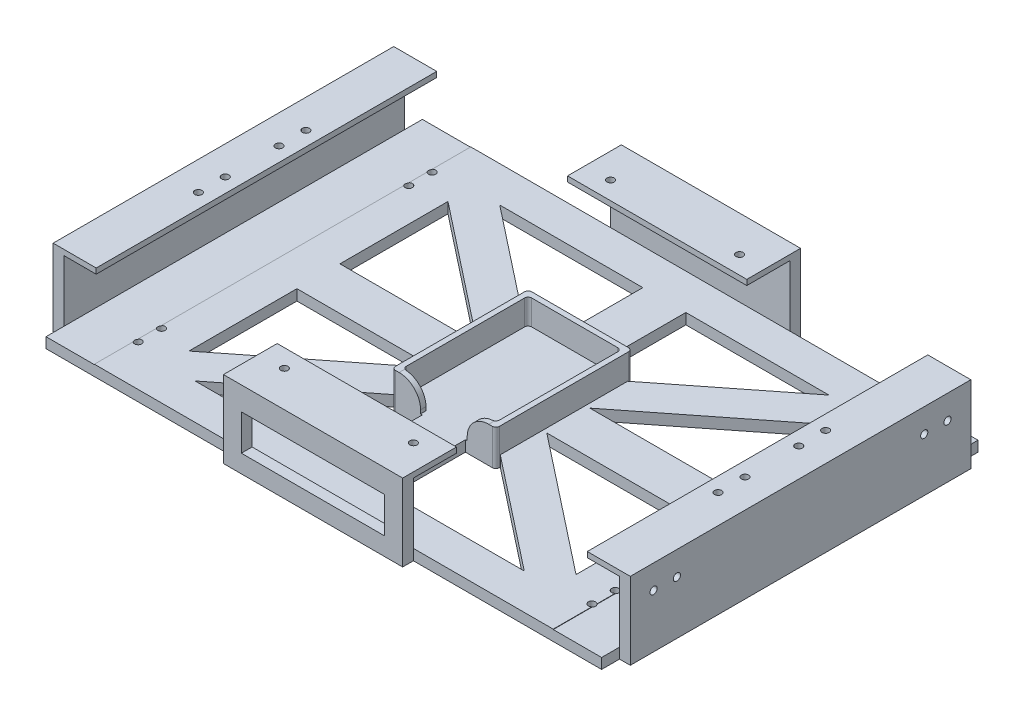
SolidWorks part; units mm, degrees
ref_plane "Front Plane" through (0, 0, 0) normal (0, 0, 1) x (1, 0, 0)
ref_plane "Top Plane" through (0, 0, 0) normal (0, 1, 0) x (1, 0, 0)
ref_plane "Right Plane" through (0, 0, 0) normal (1, 0, 0) x (0, 0, -1)
sketch "Sketch1" plane through (0, 0, 0) normal (0, 1, 0) x (1, 0, 0)
  line L1 (-77.5, -52.5) -> (77.5, -52.5)
  line L2 (-77.5, -52.5) -> (-77.5, 52.5)
  line L3 (-77.5, 52.5) -> (77.5, 52.5)
  line L4 (77.5, -52.5) -> (77.5, 52.5)
  line L5 (-77.5, -52.5) -> (77.5, 52.5) construction
  line L6 (-77.5, 52.5) -> (77.5, -52.5) construction
  line L7 (-77.5, -52.5) -> (-64, -52.5)
  line L8 (-77.5, -52.5) -> (-77.5, 52.5)
  line L9 (-77.5, 52.5) -> (-64, 52.5)
  line L10 (-64, -52.5) -> (-64, 52.5)
  line L11 (77.5, -52.5) -> (64, -52.5)
  line L12 (77.5, -52.5) -> (77.5, 52.5)
  line L13 (77.5, 52.5) -> (64, 52.5)
  line L14 (64, -52.5) -> (64, 52.5)
  point P0 (0, 0)
  dimension "D1" = 155
  dimension "D2" = 105
  dimension "D3" = 13.5
  dimension "D4" = 13.5
extrude "Boss-Extrude1" add sketch "Sketch1" along normal blind 3 contours L1 L14 L3 L10
sketch "Sketch2" plane through (0, 0, 0) normal (0, 1, 0) x (1, 0, 0)
  line L0 (-64, 52.5) -> (64, 52.5) construction
  line L1 (-64, 52.5) -> (-77.5, 52.5)
  line L2 (-64, 52.5) -> (-64, -52.5)
  line L3 (-64, -52.5) -> (-77.5, -52.5)
  line L4 (-77.5, 52.5) -> (-77.5, -52.5)
  line L5 (64, -52.5) -> (77.5, -52.5)
  line L6 (64, -52.5) -> (64, 52.5)
  line L7 (64, 52.5) -> (77.5, 52.5)
  line L8 (77.5, -52.5) -> (77.5, 52.5)
  dimension "D1" = 105
  dimension "D2" = 105
  dimension "D3" = 13.5
  dimension "D4" = 13.5
extrude "Boss-Extrude2" add sketch "Sketch2" along normal blind 2.9
sketch "Sketch3" plane through (0, 0, 0) normal (0, 1, 0) x (1, 0, 0)
  line L0 (-77.5, 52.5) -> (-77.5, -52.5) construction
  line L1 (-77.5, 47.5) -> (-80.5, 47.5)
  line L2 (-77.5, 47.5) -> (-77.5, -47.5)
  line L3 (-77.5, -47.5) -> (-80.5, -47.5)
  line L4 (-80.5, 47.5) -> (-80.5, -47.5)
  line L5 (77.5, -52.5) -> (77.5, 52.5) construction
  line L6 (77.5, -47.5) -> (80.5, -47.5)
  line L7 (77.5, -47.5) -> (77.5, 47.5)
  line L8 (77.5, 47.5) -> (80.5, 47.5)
  line L9 (80.5, -47.5) -> (80.5, 47.5)
  line L10 (-77.5, -52.5) -> (-64, -52.5) construction
  dimension "D1" = 95
  dimension "D2" = 5
  dimension "D3" = 0
  dimension "D4" = 0
  dimension "D5" = 3
  dimension "D6" = 3
sketch "Sketch4" plane through (0, 0, 0) normal (0, 1, 0) x (1, 0, 0)
  line L0 (-64, -52.5) -> (64, -52.5) construction
  line L1 (-25, -52.5) -> (25, -52.5)
  line L2 (0, -52.5) -> (0, -55.5)
  line L3 (-25, -55.5) -> (25, -55.5)
  line L4 (25, -52.5) -> (25, -55.5)
  line L5 (0, 0) -> (0, -14.14) construction
  line L6 (0, -14.14) -> (0, 0) construction
  line L7 (0, 0) -> (18.2172, 0) construction
  line L8 (-25, -52.5) -> (-25, -55.5)
  line L9 (-25, 52.5) -> (-25, 55.5)
  line L10 (-25, 52.5) -> (25, 52.5)
  line L11 (25, 52.5) -> (25, 55.5)
  line L12 (-25, 55.5) -> (25, 55.5)
  dimension "D1" = 25
  dimension "D2" = 3
sketch "Sketch5" plane through (0, 3, 0) normal (0, 1, 0) x (1, 0, 0)
  line L0 (-6.5, -17.5) -> (-6.5, -19)
  line L1 (-13, -17.5) -> (13, -17.5)
  line L2 (-13, -17.5) -> (-13, 17.5)
  line L3 (-13, 17.5) -> (13, 17.5)
  line L4 (13, -17.5) -> (13, 17.5)
  line L5 (-13, -17.5) -> (13, 17.5) construction
  line L6 (-13, 17.5) -> (13, -17.5) construction
  line L7 (-14.5, -19) -> (14.5, -19)
  line L8 (-14.5, -19) -> (-14.5, 19)
  line L9 (-14.5, 19) -> (14.5, 19)
  line L10 (14.5, -19) -> (14.5, 19)
  line L11 (-14.5, -19) -> (14.5, 19) construction
  line L12 (-14.5, 19) -> (14.5, -19) construction
  line L13 (6.5, -17.5) -> (6.5, -19)
  line L14 (0, 0) -> (0, -10.4966)
  point P0 (0, 0)
  point P6 (0, 0)
  dimension "D1" = 26
  dimension "D2" = 35
  dimension "D3" = 1.5
  dimension "D4" = 1.5
  dimension "D5" = 8
extrude "Boss-Extrude9" add sketch "Sketch5" along normal blind 7 contours L1 L13 L7 L10 L9 L8 L0 L2 L3 L4
fillet "Fillet1" radius 6 2 edges at (-6.5, 10, 18.25) (6.5, 10, 18.25)
fillet "Fillet2" radius 1 8 edges at (-13, 6.5, 17.5) (13, 6.5, 17.5) (-13, 6.5, -17.5) (14.5, 6.5, -19) (14.5, 6.5, 19) (13, 6.5, -17.5) (-14.5, 6.5, -19) (-14.5, 6.5, 19)
sketch "Sketch10" plane through (0, 3, 0) normal (0, 1, 0) x (1, 0, 0)
  line L0 (-64, -52.5) -> (-64, 52.5) construction
  line L1 (-54, -42.5) -> (54, -42.5)
  line L2 (-54, -42.5) -> (-54, 42.5)
  line L3 (-54, 42.5) -> (54, 42.5)
  line L4 (54, -42.5) -> (54, 42.5)
  line L5 (-54, -42.5) -> (54, 42.5) construction
  line L6 (-54, 42.5) -> (54, -42.5) construction
  line L7 (-64, 52.5) -> (64, 52.5) construction
  line L8 (-54, 36.1372) -> (45.9155, -42.5)
  line L9 (-45.9155, -42.5) -> (54, 36.1372)
  line L10 (-54, -36.1372) -> (45.9155, 42.5)
  line L11 (-45.9155, 42.5) -> (54, -36.1372)
  line L12 (-6.5, -19) -> (6.5, -19)
  line L13 (-54, -6) -> (54, -6)
  line L14 (-54, -6) -> (-54, 6)
  line L15 (-54, 6) -> (54, 6)
  line L16 (54, -6) -> (54, 6)
  line L17 (-54, -6) -> (54, 6) construction
  line L18 (-54, 6) -> (54, -6) construction
  line L19 (-6, 42.5) -> (6, 42.5)
  line L20 (-6, 42.5) -> (-6, -42.5)
  line L21 (-6, -42.5) -> (6, -42.5)
  line L22 (6, 42.5) -> (6, -42.5)
  line L23 (-6, 42.5) -> (6, -42.5) construction
  line L24 (-6, -42.5) -> (6, 42.5) construction
  point P0 (0, 0)
  point P18 (0, 0)
  point P23 (0, 0)
  line M19 (-6.5, -19) -> (-13.5, -19)
  arc M20 (-13.5, -19) -> (-14.5, -18) centre (-13.5, -18) cw
  line M21 (-14.5, -18) -> (-14.5, 18)
  arc M22 (-14.5, 18) -> (-13.5, 19) centre (-13.5, 18) cw
  line M23 (-13.5, 19) -> (13.5, 19)
  arc M24 (13.5, 19) -> (14.5, 18) centre (13.5, 18) cw
  line M25 (14.5, 18) -> (14.5, -18)
  arc M26 (14.5, -18) -> (13.5, -19) centre (13.5, -18) cw
  line M27 (13.5, -19) -> (6.5, -19)
  dimension "D1" = 10
  dimension "D2" = 10
  dimension "D3" = 5
  dimension "D4" = 5
  dimension "D5" = 10
  dimension "D6" = 10
  dimension "D7" = 12
  dimension "D8" = 12
extrude "Cut-Extrude1" cut sketch "Sketch10" against normal blind 7 contours L2 L15 L8 | L20 L3 L11 M21 M22 M23 | L3 L22 L10 M23 M24 M25 | L9 L15 L4 | L13 L11 L4 | L12 L22 L1 L8 M25 M26 M27 | L20 L12 L9 L1 M19 M20 M21 | L13 L2 L10
extrude "Boss-Extrude10" add sketch "Sketch3" along normal blind 20
sketch "Sketch11" plane through (0, 3, 0) normal (0, 1, 0) x (1, 0, 0)
  line L0 (-64, -52.5) -> (-64, -42.5)
  line L1 (-64, -52.5) -> (-64, 52.5) construction
  line L2 (-64, -42.5) -> (-63.3, -42.5)
  line L3 (-63.3, -39.5) -> (-63.3, -36)
  line L4 (-63.3, -33) -> (-64, -33)
  line L5 (0, 0) -> (29.0728, 0) construction
  line L6 (29.0728, 0) -> (0, 0) construction
  line L7 (0, 0) -> (0, 24.7559) construction
  line L8 (-63.3, 33) -> (-64, 33)
  line L9 (-63.3, 39.5) -> (-63.3, 36)
  line L10 (-64, 42.5) -> (-63.3, 42.5)
  line L11 (64, 42.5) -> (63.3, 42.5)
  line L12 (63.3, 39.5) -> (63.3, 36)
  line L13 (63.3, 33) -> (64, 33)
  line L14 (63.3, -33) -> (64, -33)
  line L15 (63.3, -39.5) -> (63.3, -36)
  line L16 (64, -42.5) -> (63.3, -42.5)
  arc A0 (-63.3, -42.5) -> (-63.3, -39.5) centre (-63.3, -41) ccw
  circle A1 centre (-63.3, -41) radius 1
  arc A2 (-63.3, -36) -> (-63.3, -33) centre (-63.3, -34.5) ccw
  circle A3 centre (-63.3, -34.5) radius 1
  circle A4 centre (-63.3, 34.5) radius 1
  arc A5 (-63.3, 36) -> (-63.3, 33) centre (-63.3, 34.5) cw
  circle A6 centre (-63.3, 41) radius 1
  arc A7 (-63.3, 42.5) -> (-63.3, 39.5) centre (-63.3, 41) cw
  arc A8 (63.3, 42.5) -> (63.3, 39.5) centre (63.3, 41) ccw
  circle A9 centre (63.3, 41) radius 1
  arc A10 (63.3, 36) -> (63.3, 33) centre (63.3, 34.5) ccw
  circle A11 centre (63.3, 34.5) radius 1
  circle A12 centre (63.3, -34.5) radius 1
  arc A13 (63.3, -36) -> (63.3, -33) centre (63.3, -34.5) cw
  circle A14 centre (63.3, -41) radius 1
  arc A15 (63.3, -42.5) -> (63.3, -39.5) centre (63.3, -41) cw
  dimension "D3" = 1.5
  dimension "D4" = 2
  dimension "D6" = 1.5
  dimension "D7" = 2
  dimension "D1" = 10
  dimension "D2" = 0.7
  dimension "D5" = 3.5
  dimension "D8" = 6.5
extrude "Cut-Extrude2" cut sketch "Sketch11" against normal blind 20 contours A1 | A3 | A6 | A4 | A9 | A11 | A14 | A12
sketch "Sketch13" plane through (-77.5, 0, 0) normal (1, 0, 0) x (0, 0, -1)
  line L0 (-42.5, 14.8425) -> (-39.5, 14.8425)
  line L1 (-52.5, 2.9) -> (-42.5, 2.9)
  line L2 (-42.5, 2.6425) -> (-42.5, 14.8425)
  line L4 (-39.5, 14.8425) -> (-36, 14.8425)
  arc A0 (-42.5, 14.8425) -> (-39.5, 14.8425) centre (-41, 14.8425) cw
  circle A1 centre (-41, 14.8425) radius 1
  arc A2 (-36, 14.8425) -> (-33, 14.8425) centre (-34.5, 14.8425) cw
  circle A3 centre (-34.5, 14.8425) radius 1
  dimension "D3" = 1.5
  dimension "D4" = 2
  dimension "D6" = 1.5
  dimension "D7" = 2
  dimension "D1" = 10
  dimension "D2" = 12.2
  dimension "D5" = 3.5
extrude "Cut-Extrude3" cut sketch "Sketch13" against normal blind 20 contours A1 | A3
mirror "Mirror1" about plane through (0, 0, 0) normal (0, 0, 1) of "Cut-Extrude3" second plane through (0, 0, 0) second plane normal (1, 0, 0)
extrude "Boss-Extrude11" add sketch "Sketch4" along normal blind 20 contours L12 L9 L10 L11 | L1 L8 L3 L2 | L4 L1 L2 L3
sketch "Sketch14" plane through (0, 0, 55.5) normal (0, 0, 1) x (1, 0, 0)
  line L0 (0, 0) -> (0, 20) construction
  line L1 (-25, 20) -> (25, 20) construction
  line L3 (25, 20) -> (25, 0) construction
  line L4 (25, 10) -> (-25, 10) construction
  line L5 (-25, 20) -> (-25, 0) construction
  line L6 (-20, 5) -> (20, 5)
  line L7 (-20, 5) -> (-20, 15)
  line L8 (-20, 15) -> (20, 15)
  line L9 (20, 5) -> (20, 15)
  line L10 (-20, 5) -> (20, 15) construction
  line L11 (-20, 15) -> (20, 5) construction
  point P11 (0, 10)
  dimension "D1" = 10
  dimension "D2" = 40
extrude "Cut-Extrude4" cut sketch "Sketch14" against normal up to next
sketch "Sketch15" plane through (0, 20, 0) normal (0, 1, 0) x (1, 0, 0)
  line L1 (-25, -55.5) -> (25, -55.5)
  line L2 (-25, -55.5) -> (-25, -40.5)
  line L3 (-25, -40.5) -> (25, -40.5)
  line L4 (25, -55.5) -> (25, -40.5)
  dimension "D1" = 15
  dimension "D2" = 50
extrude "Boss-Extrude12" add sketch "Sketch15" along normal blind 1.5
sketch "Sketch17" plane through (0, 21.5, 0) normal (0, 1, 0) x (1, 0, 0)
  line L0 (0, -40.5) -> (0, -45.5)
  line L1 (25, -40.5) -> (-25, -40.5) construction
  line L2 (0, -45.5) -> (18, -45.5)
  circle A0 centre (18, -45.5) radius 1
  circle A1 centre (-18, -45.5) radius 1
  point P7 (0, 0)
  point P10 (0, 0)
  point P11 (0, 0)
  dimension "D3" = 2
  dimension "D1" = 5
  dimension "D2" = 18
extrude "Cut-Extrude5" cut sketch "Sketch17" against normal blind 1.5 contours A0 | A1
mirror "Mirror2" about plane through (0, 0, 0) normal (0, 0, 1) of "Cut-Extrude5", "Boss-Extrude12"
sketch "Sketch18" plane through (0, 20, 0) normal (0, 1, 0) x (1, 0, 0)
  line L0 (-80.5, -47.5) -> (-77.5, -47.5) construction
  line L1 (-80.5, 47.5) -> (-68.5, 47.5)
  line L2 (-80.5, 47.5) -> (-80.5, -47.5)
  line L3 (-80.5, -47.5) -> (-68.5, -47.5)
  line L4 (-68.5, 47.5) -> (-68.5, -47.5)
  line L5 (-68.5, 0) -> (-80.5, 0)
  line L6 (-68.5, 0) -> (-72.5, 0)
  line L7 (-72.5, 0) -> (-72.5, -15)
  line L8 (-72.5, 0) -> (-72.5, 7.5)
  line L9 (-72.5, 7.5) -> (-72.5, 15)
  circle A0 centre (-72.5, -15) radius 1
  circle A1 centre (-72.5, -7.5) radius 1
  circle A2 centre (-72.5, 7.5) radius 1
  circle A3 centre (-72.5, 15) radius 1
  dimension "D4" = 2
  dimension "D6" = 2
  dimension "D8" = 2
  dimension "D10" = 2
  dimension "D1" = 0
  dimension "D2" = 12
  dimension "D3" = 4
  dimension "D5" = 15
  dimension "D7" = 7.5
  dimension "D9" = 7.5
extrude "Boss-Extrude13" add sketch "Sketch18" along normal blind 1.5
mirror "Mirror3" about plane through (0, 0, 0) normal (1, 0, 0) of "Boss-Extrude13"
